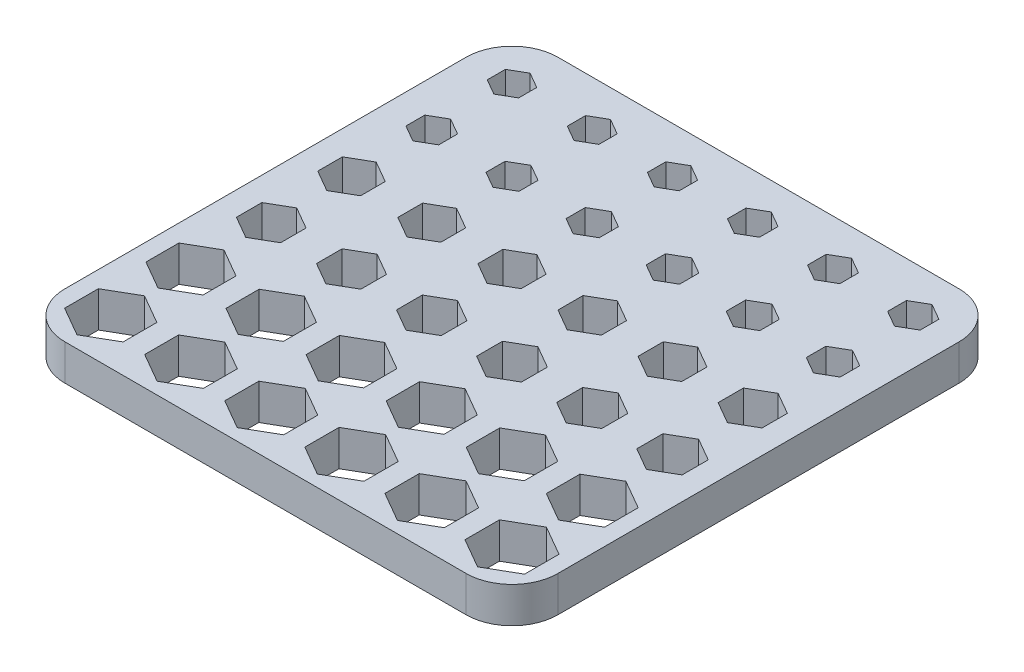
SolidWorks part; units mm, degrees
ref_plane "Front Plane" through (0, 0, 0) normal (0, 0, 1) x (1, 0, 0)
ref_plane "Top Plane" through (0, 0, 0) normal (0, 1, 0) x (1, 0, 0)
ref_plane "Right Plane" through (0, 0, 0) normal (1, 0, 0) x (0, 0, -1)
sketch "Sketch1" plane through (0, 0, 0) normal (0, 1, 0) x (1, 0, 0)
  line L0 (10.16, 27.94) -> (10.16, 10.16) construction
  line L1 (0, 0) -> (109.22, 0)
  line L2 (0, 0) -> (0, 109.22)
  line L3 (0, 109.22) -> (109.22, 109.22)
  line L4 (109.22, 0) -> (109.22, 109.22)
  line L17 (10.16, 10.16) -> (27.94, 10.16) construction
  line L18 (27.94, 10.16) -> (10.16, 10.16) construction
  line L20 (10.16, 103.0726) -> (6.685, 101.0663)
  line L21 (6.685, 101.0663) -> (6.685, 97.0537)
  line L22 (6.685, 97.0537) -> (10.16, 95.0474)
  line L23 (10.16, 95.0474) -> (13.635, 97.0537)
  line L24 (13.635, 97.0537) -> (13.635, 101.0663)
  line L25 (13.635, 101.0663) -> (10.16, 103.0726)
  line L28 (27.94, 103.1015) -> (24.44, 101.0807)
  line L29 (24.44, 101.0807) -> (24.44, 97.0393)
  line L30 (24.44, 97.0393) -> (27.94, 95.0185)
  line L31 (27.94, 95.0185) -> (31.44, 97.0393)
  line L32 (31.44, 97.0393) -> (31.44, 101.0807)
  line L33 (31.44, 101.0807) -> (27.94, 103.1015)
  line L35 (45.72, 103.1303) -> (42.195, 101.0952)
  line L36 (42.195, 101.0952) -> (42.195, 97.0248)
  line L37 (42.195, 97.0248) -> (45.72, 94.9897)
  line L38 (45.72, 94.9897) -> (49.245, 97.0248)
  line L39 (49.245, 97.0248) -> (49.245, 101.0952)
  line L40 (49.245, 101.0952) -> (45.72, 103.1303)
  line L42 (63.5, 103.1592) -> (59.95, 101.1096)
  line L43 (59.95, 101.1096) -> (59.95, 97.0104)
  line L44 (59.95, 97.0104) -> (63.5, 94.9608)
  line L45 (63.5, 94.9608) -> (67.05, 97.0104)
  line L46 (67.05, 97.0104) -> (67.05, 101.1096)
  line L47 (67.05, 101.1096) -> (63.5, 103.1592)
  line L49 (81.28, 103.1881) -> (77.705, 101.124)
  line L50 (77.705, 101.124) -> (77.705, 96.996)
  line L51 (77.705, 96.996) -> (81.28, 94.9319)
  line L52 (81.28, 94.9319) -> (84.855, 96.996)
  line L53 (84.855, 96.996) -> (84.855, 101.124)
  line L54 (84.855, 101.124) -> (81.28, 103.1881)
  line L56 (99.06, 103.2169) -> (95.46, 101.1385)
  line L57 (95.46, 101.1385) -> (95.46, 96.9815)
  line L58 (95.46, 96.9815) -> (99.06, 94.9031)
  line L59 (99.06, 94.9031) -> (102.66, 96.9815)
  line L60 (102.66, 96.9815) -> (102.66, 101.1385)
  line L61 (102.66, 101.1385) -> (99.06, 103.2169)
  line L63 (10.16, 85.4658) -> (6.535, 83.3729)
  line L64 (6.535, 83.3729) -> (6.535, 79.1871)
  line L65 (6.535, 79.1871) -> (10.16, 77.0942)
  line L66 (10.16, 77.0942) -> (13.785, 79.1871)
  line L67 (13.785, 79.1871) -> (13.785, 83.3729)
  line L68 (13.785, 83.3729) -> (10.16, 85.4658)
  line L70 (27.94, 85.4947) -> (24.29, 83.3873)
  line L71 (24.29, 83.3873) -> (24.29, 79.1727)
  line L72 (24.29, 79.1727) -> (27.94, 77.0653)
  line L73 (27.94, 77.0653) -> (31.59, 79.1727)
  line L74 (31.59, 79.1727) -> (31.59, 83.3873)
  line L75 (31.59, 83.3873) -> (27.94, 85.4947)
  line L77 (45.72, 85.5235) -> (42.045, 83.4018)
  line L78 (42.045, 83.4018) -> (42.045, 79.1582)
  line L79 (42.045, 79.1582) -> (45.72, 77.0365)
  line L80 (45.72, 77.0365) -> (49.395, 79.1582)
  line L81 (49.395, 79.1582) -> (49.395, 83.4018)
  line L82 (49.395, 83.4018) -> (45.72, 85.5235)
  line L84 (63.5, 85.5524) -> (59.8, 83.4162)
  line L85 (59.8, 83.4162) -> (59.8, 79.1438)
  line L86 (59.8, 79.1438) -> (63.5, 77.0076)
  line L87 (63.5, 77.0076) -> (67.2, 79.1438)
  line L88 (67.2, 79.1438) -> (67.2, 83.4162)
  line L89 (67.2, 83.4162) -> (63.5, 85.5524)
  line L91 (81.28, 85.5813) -> (77.555, 83.4306)
  line L92 (77.555, 83.4306) -> (77.555, 79.1294)
  line L93 (77.555, 79.1294) -> (81.28, 76.9787)
  line L94 (81.28, 76.9787) -> (85.005, 79.1294)
  line L95 (85.005, 79.1294) -> (85.005, 83.4306)
  line L96 (85.005, 83.4306) -> (81.28, 85.5813)
  line L97 (99.06, 85.6101) -> (95.31, 83.4451)
  line L98 (95.31, 83.4451) -> (95.31, 79.1149)
  line L99 (95.31, 79.1149) -> (99.06, 76.9499)
  line L100 (99.06, 76.9499) -> (102.81, 79.1149)
  line L101 (102.81, 79.1149) -> (102.81, 83.4451)
  line L102 (102.81, 83.4451) -> (99.06, 85.6101)
  line L103 (10.16, 68.9699) -> (5.4229, 66.235)
  line L104 (5.4229, 66.235) -> (5.4229, 60.765)
  line L105 (5.4229, 60.765) -> (10.16, 58.0301)
  line L106 (10.16, 58.0301) -> (14.8971, 60.765)
  line L107 (14.8971, 60.765) -> (14.8971, 66.235)
  line L108 (14.8971, 66.235) -> (10.16, 68.9699)
  line L109 (27.94, 68.9993) -> (23.1775, 66.2496)
  line L110 (23.1775, 66.2496) -> (23.1775, 60.7504)
  line L111 (23.1775, 60.7504) -> (27.94, 58.0007)
  line L112 (27.94, 58.0007) -> (32.7025, 60.7504)
  line L113 (32.7025, 60.7504) -> (32.7025, 66.2496)
  line L114 (32.7025, 66.2496) -> (27.94, 68.9993)
  line L115 (45.72, 69.0286) -> (40.9321, 66.2643)
  line L116 (40.9321, 66.2643) -> (40.9321, 60.7357)
  line L117 (40.9321, 60.7357) -> (45.72, 57.9714)
  line L118 (45.72, 57.9714) -> (50.5079, 60.7357)
  line L119 (50.5079, 60.7357) -> (50.5079, 66.2643)
  line L120 (50.5079, 66.2643) -> (45.72, 69.0286)
  line L121 (63.5, 69.0579) -> (58.6867, 66.279)
  line L122 (58.6867, 66.279) -> (58.6867, 60.721)
  line L123 (58.6867, 60.721) -> (63.5, 57.9421)
  line L124 (63.5, 57.9421) -> (68.3133, 60.721)
  line L125 (68.3133, 60.721) -> (68.3133, 66.279)
  line L126 (68.3133, 66.279) -> (63.5, 69.0579)
  line L127 (81.28, 69.0872) -> (76.4413, 66.2936)
  line L128 (76.4413, 66.2936) -> (76.4413, 60.7064)
  line L129 (76.4413, 60.7064) -> (81.28, 57.9128)
  line L130 (81.28, 57.9128) -> (86.1187, 60.7064)
  line L131 (86.1187, 60.7064) -> (86.1187, 66.2936)
  line L132 (86.1187, 66.2936) -> (81.28, 69.0872)
  line L133 (99.06, 69.1166) -> (94.1959, 66.3083)
  line L134 (94.1959, 66.3083) -> (94.1959, 60.6917)
  line L135 (94.1959, 60.6917) -> (99.06, 57.8834)
  line L136 (99.06, 57.8834) -> (103.9241, 60.6917)
  line L137 (103.9241, 60.6917) -> (103.9241, 66.3083)
  line L138 (103.9241, 66.3083) -> (99.06, 69.1166)
  line L139 (10.16, 51.3659) -> (5.2705, 48.543)
  line L140 (5.2705, 48.543) -> (5.2705, 42.897)
  line L141 (5.2705, 42.897) -> (10.16, 40.0741)
  line L142 (10.16, 40.0741) -> (15.0495, 42.897)
  line L143 (15.0495, 42.897) -> (15.0495, 48.543)
  line L144 (15.0495, 48.543) -> (10.16, 51.3659)
  line L145 (27.94, 51.3952) -> (23.0251, 48.5576)
  line L146 (23.0251, 48.5576) -> (23.0251, 42.8824)
  line L147 (23.0251, 42.8824) -> (27.94, 40.0448)
  line L148 (27.94, 40.0448) -> (32.8549, 42.8824)
  line L149 (32.8549, 42.8824) -> (32.8549, 48.5576)
  line L150 (32.8549, 48.5576) -> (27.94, 51.3952)
  line L151 (45.72, 51.4246) -> (40.7797, 48.5723)
  line L152 (40.7797, 48.5723) -> (40.7797, 42.8677)
  line L153 (40.7797, 42.8677) -> (45.72, 40.0154)
  line L154 (45.72, 40.0154) -> (50.6603, 42.8677)
  line L155 (50.6603, 42.8677) -> (50.6603, 48.5723)
  line L156 (50.6603, 48.5723) -> (45.72, 51.4246)
  line L157 (63.5, 51.4539) -> (58.5343, 48.5869)
  line L158 (58.5343, 48.5869) -> (58.5343, 42.8531)
  line L159 (58.5343, 42.8531) -> (63.5, 39.9861)
  line L160 (63.5, 39.9861) -> (68.4657, 42.8531)
  line L161 (68.4657, 42.8531) -> (68.4657, 48.5869)
  line L162 (68.4657, 48.5869) -> (63.5, 51.4539)
  line L163 (81.28, 51.4832) -> (76.2889, 48.6016)
  line L164 (76.2889, 48.6016) -> (76.2889, 42.8384)
  line L165 (76.2889, 42.8384) -> (81.28, 39.9568)
  line L166 (81.28, 39.9568) -> (86.2711, 42.8384)
  line L167 (86.2711, 42.8384) -> (86.2711, 48.6016)
  line L168 (86.2711, 48.6016) -> (81.28, 51.4832)
  line L169 (99.06, 51.5126) -> (94.0435, 48.6163)
  line L170 (94.0435, 48.6163) -> (94.0435, 42.8237)
  line L171 (94.0435, 42.8237) -> (99.06, 39.9274)
  line L172 (99.06, 39.9274) -> (104.0765, 42.8237)
  line L173 (104.0765, 42.8237) -> (104.0765, 48.6163)
  line L174 (104.0765, 48.6163) -> (99.06, 51.5126)
  line L175 (10.16, 35.243) -> (3.8354, 31.5915)
  line L176 (3.8354, 31.5915) -> (3.8354, 24.2885)
  line L177 (3.8354, 24.2885) -> (10.16, 20.637)
  line L178 (10.16, 20.637) -> (16.4846, 24.2885)
  line L179 (16.4846, 24.2885) -> (16.4846, 31.5915)
  line L180 (16.4846, 31.5915) -> (10.16, 35.243)
  line L181 (10.16, 17.639) -> (3.683, 13.8995)
  line L182 (3.683, 13.8995) -> (3.683, 6.4205)
  line L183 (3.683, 6.4205) -> (10.16, 2.681)
  line L184 (10.16, 2.681) -> (16.637, 6.4205)
  line L185 (16.637, 6.4205) -> (16.637, 13.8995)
  line L186 (16.637, 13.8995) -> (10.16, 17.639)
  line L187 (27.94, 35.2723) -> (21.59, 31.6062)
  line L188 (21.59, 31.6062) -> (21.59, 24.2738)
  line L189 (21.59, 24.2738) -> (27.94, 20.6077)
  line L190 (27.94, 20.6077) -> (34.29, 24.2738)
  line L191 (34.29, 24.2738) -> (34.29, 31.6062)
  line L192 (34.29, 31.6062) -> (27.94, 35.2723)
  line L193 (27.94, 17.6683) -> (21.4376, 13.9142)
  line L194 (21.4376, 13.9142) -> (21.4376, 6.4058)
  line L195 (21.4376, 6.4058) -> (27.94, 2.6517)
  line L196 (27.94, 2.6517) -> (34.4424, 6.4058)
  line L197 (34.4424, 6.4058) -> (34.4424, 13.9142)
  line L198 (34.4424, 13.9142) -> (27.94, 17.6683)
  line L199 (45.72, 35.3017) -> (39.3446, 31.6208)
  line L200 (39.3446, 31.6208) -> (39.3446, 24.2592)
  line L201 (39.3446, 24.2592) -> (45.72, 20.5783)
  line L202 (45.72, 20.5783) -> (52.0954, 24.2592)
  line L203 (52.0954, 24.2592) -> (52.0954, 31.6208)
  line L204 (52.0954, 31.6208) -> (45.72, 35.3017)
  line L205 (45.72, 17.6977) -> (39.1922, 13.9288)
  line L206 (39.1922, 13.9288) -> (39.1922, 6.3912)
  line L207 (39.1922, 6.3912) -> (45.72, 2.6223)
  line L208 (45.72, 2.6223) -> (52.2478, 6.3912)
  line L209 (52.2478, 6.3912) -> (52.2478, 13.9288)
  line L210 (52.2478, 13.9288) -> (45.72, 17.6977)
  line L211 (63.5, 35.331) -> (57.0992, 31.6355)
  line L212 (57.0992, 31.6355) -> (57.0992, 24.2445)
  line L213 (57.0992, 24.2445) -> (63.5, 20.549)
  line L214 (63.5, 20.549) -> (69.9008, 24.2445)
  line L215 (69.9008, 24.2445) -> (69.9008, 31.6355)
  line L216 (69.9008, 31.6355) -> (63.5, 35.331)
  line L217 (63.5, 17.727) -> (56.9468, 13.9435)
  line L218 (56.9468, 13.9435) -> (56.9468, 6.3765)
  line L219 (56.9468, 6.3765) -> (63.5, 2.593)
  line L220 (63.5, 2.593) -> (70.0532, 6.3765)
  line L221 (70.0532, 6.3765) -> (70.0532, 13.9435)
  line L222 (70.0532, 13.9435) -> (63.5, 17.727)
  line L223 (81.28, 35.3603) -> (74.8538, 31.6502)
  line L224 (74.8538, 31.6502) -> (74.8538, 24.2298)
  line L225 (74.8538, 24.2298) -> (81.28, 20.5197)
  line L226 (81.28, 20.5197) -> (87.7062, 24.2298)
  line L227 (87.7062, 24.2298) -> (87.7062, 31.6502)
  line L228 (87.7062, 31.6502) -> (81.28, 35.3603)
  line L229 (81.28, 17.7563) -> (74.7014, 13.9582)
  line L230 (74.7014, 13.9582) -> (74.7014, 6.3618)
  line L231 (74.7014, 6.3618) -> (81.28, 2.5637)
  line L232 (81.28, 2.5637) -> (87.8586, 6.3618)
  line L233 (87.8586, 6.3618) -> (87.8586, 13.9582)
  line L234 (87.8586, 13.9582) -> (81.28, 17.7563)
  line L235 (99.06, 17.7856) -> (92.456, 13.9728)
  line L236 (92.456, 13.9728) -> (92.456, 6.3472)
  line L237 (92.456, 6.3472) -> (99.06, 2.5344)
  line L238 (99.06, 2.5344) -> (105.664, 6.3472)
  line L239 (105.664, 6.3472) -> (105.664, 13.9728)
  line L240 (105.664, 13.9728) -> (99.06, 17.7856)
  line L241 (99.06, 35.3897) -> (92.6084, 31.6648)
  line L242 (92.6084, 31.6648) -> (92.6084, 24.2152)
  line L243 (92.6084, 24.2152) -> (99.06, 20.4903)
  line L244 (99.06, 20.4903) -> (105.5116, 24.2152)
  line L245 (105.5116, 24.2152) -> (105.5116, 31.6648)
  line L246 (105.5116, 31.6648) -> (99.06, 35.3897)
  circle A0 centre (10.16, 99.06) radius 3.475 construction
  circle A1 centre (27.94, 99.06) radius 3.5 construction
  circle A2 centre (45.72, 99.06) radius 3.525 construction
  circle A3 centre (63.5, 99.06) radius 3.55 construction
  circle A4 centre (81.28, 99.06) radius 3.575 construction
  circle A5 centre (99.06, 99.06) radius 3.6 construction
  circle A6 centre (10.16, 81.28) radius 3.625 construction
  circle A7 centre (27.94, 81.28) radius 3.65 construction
  circle A8 centre (45.72, 81.28) radius 3.675 construction
  circle A9 centre (63.5, 81.28) radius 3.7 construction
  circle A10 centre (81.28, 81.28) radius 3.725 construction
  circle A11 centre (99.06, 81.28) radius 3.75 construction
  circle A12 centre (10.16, 63.5) radius 4.7371 construction
  circle A13 centre (27.94, 63.5) radius 4.7625 construction
  circle A14 centre (45.72, 63.5) radius 4.7879 construction
  circle A15 centre (63.5, 63.5) radius 4.8133 construction
  circle A16 centre (81.28, 63.5) radius 4.8387 construction
  circle A17 centre (99.06, 63.5) radius 4.8641 construction
  circle A18 centre (10.16, 45.72) radius 4.8895 construction
  circle A19 centre (27.94, 45.72) radius 4.9149 construction
  circle A20 centre (45.72, 45.72) radius 4.9403 construction
  circle A21 centre (63.5, 45.72) radius 4.9657 construction
  circle A22 centre (81.28, 45.72) radius 4.9911 construction
  circle A23 centre (99.06, 45.72) radius 5.0165 construction
  circle A24 centre (10.16, 27.94) radius 6.3246 construction
  circle A25 centre (10.16, 10.16) radius 6.477 construction
  circle A26 centre (27.94, 27.94) radius 6.35 construction
  circle A27 centre (27.94, 10.16) radius 6.5024 construction
  circle A28 centre (45.72, 27.94) radius 6.3754 construction
  circle A29 centre (45.72, 10.16) radius 6.5278 construction
  circle A30 centre (63.5, 27.94) radius 6.4008 construction
  circle A31 centre (63.5, 10.16) radius 6.5532 construction
  circle A32 centre (81.28, 27.94) radius 6.4262 construction
  circle A33 centre (81.28, 10.16) radius 6.5786 construction
  circle A34 centre (99.06, 10.16) radius 6.604 construction
  circle A35 centre (99.06, 27.94) radius 6.4516 construction
  point P4 (10.16, 10.16)
  point P5 (10.16, 45.72)
  point P7 (27.94, 45.72)
  point P8 (27.94, 10.16)
  point P9 (45.72, 10.16)
  point P10 (63.5, 10.16)
  point P11 (81.28, 10.16)
  point P12 (99.06, 10.16)
  point P13 (27.94, 27.94)
  point P14 (45.72, 27.94)
  point P15 (63.5, 27.94)
  point P16 (81.28, 27.94)
  point P17 (99.06, 27.94)
  point P18 (45.72, 45.72)
  point P19 (63.5, 45.72)
  point P20 (81.28, 45.72)
  point P21 (99.06, 45.72)
  point P22 (10.16, 63.5)
  point P23 (27.94, 63.5)
  point P24 (45.72, 63.5)
  point P25 (63.5, 63.5)
  point P26 (81.28, 63.5)
  point P27 (99.06, 63.5)
  point P28 (10.16, 27.94)
  point P29 (10.16, 81.28)
  point P30 (27.94, 81.28)
  point P32 (45.72, 81.28)
  point P33 (63.5, 81.28)
  point P34 (81.28, 81.28)
  point P35 (99.06, 81.28)
  point P36 (10.16, 99.06)
  point P37 (27.94, 99.06)
  point P38 (45.72, 99.06)
  point P39 (63.5, 99.06)
  point P40 (81.28, 99.06)
  point P41 (99.06, 99.06)
  dimension "D8" = 6.95
  dimension "D9" = 7
  dimension "D10" = 7.05
  dimension "D11" = 7.1
  dimension "D12" = 7.15
  dimension "D13" = 7.2
  dimension "D14" = 7.25
  dimension "D15" = 7.3
  dimension "D16" = 7.35
  dimension "D17" = 7.4
  dimension "D18" = 7.45
  dimension "D19" = 7.5
  dimension "D20" = 9.4742
  dimension "D21" = 9.525
  dimension "D22" = 9.5758
  dimension "D23" = 9.6266
  dimension "D24" = 9.6774
  dimension "D25" = 9.7282
  dimension "D26" = 9.779
  dimension "D27" = 9.8298
  dimension "D28" = 9.8806
  dimension "D29" = 9.9314
  dimension "D30" = 9.9822
  dimension "D31" = 10.033
  dimension "D32" = 12.6492
  dimension "D33" = 12.7
  dimension "D34" = 12.7508
  dimension "D35" = 12.8016
  dimension "D36" = 12.8524
  dimension "D37" = 12.9032
  dimension "D38" = 12.954
  dimension "D39" = 13.0048
  dimension "D40" = 13.0556
  dimension "D41" = 13.1064
  dimension "D42" = 13.1572
  dimension "D43" = 13.208
  dimension "D1" = 6
  dimension "D2" = 6
  dimension "D3" = 17.78
  dimension "D4" = 10.16
  dimension "D5" = 10.16
  dimension "D6" = 10.16
  dimension "D7" = 10.16
extrude "Boss-Extrude1" add sketch "Sketch1" along normal blind 7.9375
fillet "Fillet1" radius 10.16 4 edges at (0, 3.9688, -109.22) (109.22, 3.9688, -109.22) (109.22, 3.9688, 0) (0, 3.9688, 0)
